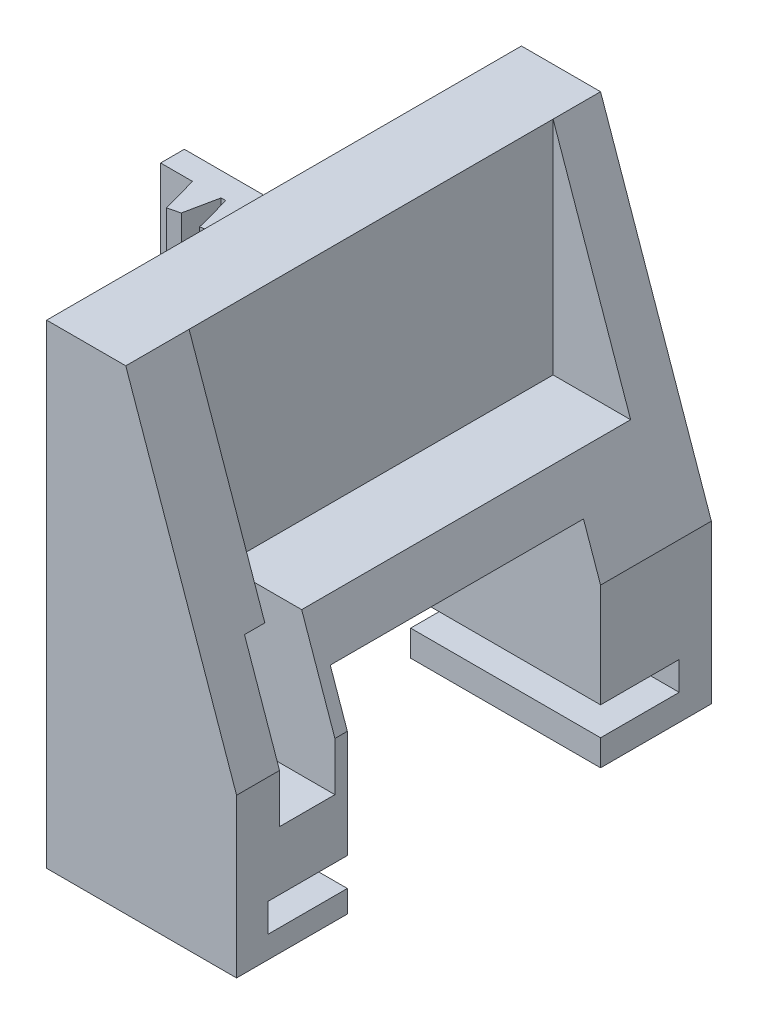
SolidWorks part; units mm, degrees
ref_plane "Front Plane" through (0, 0, 0) normal (0, 0, 1) x (1, 0, 0)
ref_plane "Top Plane" through (0, 0, 0) normal (0, 1, 0) x (1, 0, 0)
ref_plane "Right Plane" through (0, 0, 0) normal (1, 0, 0) x (0, 0, -1)
sketch "Sketch1" plane through (0, 0, 0) normal (0, 0, 1) x (1, 0, 0)
  line L0 (0, 0) -> (0, -30)
  line L1 (0, -30) -> (12, -30)
  line L2 (12, -30) -> (12, -20)
  line L3 (12, -20) -> (5, 0)
  line L4 (5, 0) -> (0, 0)
  dimension "D1" = 30
  dimension "D2" = 12
  dimension "D3" = 10
  dimension "D4" = 5
extrude "Boss-Extrude1" add sketch "Sketch1" against normal blind 30
sketch "Sketch4" plane through (0, 0, 0) normal (-1, 0, 0) x (0, 0, 1)
  line L0 (-30, 0) -> (-30, -30) construction
  line L1 (-23, -16.9179) -> (-7, -16.9179)
  line L2 (-23, -16.9179) -> (-23, -30.9179)
  line L3 (-23, -30.9179) -> (-7, -30.9179)
  line L4 (-7, -16.9179) -> (-7, -30.9179)
  point P4 (-23, -23.9179)
  dimension "D1" = 16
  dimension "D2" = 14
  dimension "D3" = 7
extrude "Cut-Extrude2" cut sketch "Sketch4" against normal blind 25 contours L2 L1 L4 L3
sketch "Sketch5" plane through (0, 0, 0) normal (-1, 0, 0) x (0, 0, 1)
  line L0 (-7, -16.9179) -> (-7, -30) construction
  line L1 (-7, -26.8) -> (-2, -26.8)
  line L2 (-7, -26.8) -> (-7, -28.6)
  line L3 (-7, -28.6) -> (-2, -28.6)
  line L4 (-2, -26.8) -> (-2, -28.6)
  line L5 (-7, -30) -> (0, -30) construction
  dimension "D1" = 1.8
  dimension "D2" = 5
  dimension "D3" = 1.4
extrude "Cut-Extrude3" cut sketch "Sketch5" against normal blind 15
ref_plane "Plane1" through (0, 0, -15.5) normal (0, 0, 1) x (1, 0, 0)
sketch "Sketch6" plane through (0, 0, -15.5) normal (0, 0, 1) x (1, 0, 0)
  line L0 (5, 0) -> (5, -14)
  line L1 (5, -14) -> (9.9, -14)
  line L2 (12, -20) -> (5, 0) construction
  line L3 (9.9, -14) -> (5, 0)
  dimension "D1" = 14
extrude "Cut-Extrude4" cut sketch "Sketch6" against normal mid plane 23
ref_plane "Plane2" through (0, -22, 0) normal (0, 1, 0) x (1, 0, 0)
sketch "Sketch7" plane through (0, -22, 0) normal (0, 1, 0) x (1, 0, 0)
  line L0 (0, 27.7) -> (-19, 27.7)
  line L1 (0, 30) -> (0, 0) construction
  line L3 (0, 27.7) -> (0, 26.2)
  line L4 (0, 26.2) -> (-0.5, 26.2)
  line L47 (-0.5, 26.2) -> (-0.9304, 24.1151)
  line L62 (-6.6, 15.5) -> (6.6, 15.5) construction
  line L108 (-19, 26.2) -> (-19, 27.7)
  line L112 (-0.9304, 24.1151) -> (-1.6865, 23.9276)
  line L113 (-2.3144, 26.2) -> (-2.597, 26.2)
  line L114 (-3.0274, 24.1151) -> (-3.7835, 23.9276)
  line L115 (-2.597, 26.2) -> (-3.0274, 24.1151)
  line L116 (-5.1244, 24.1151) -> (-5.8805, 23.9276)
  line L117 (-4.694, 26.2) -> (-5.1244, 24.1151)
  line L118 (-7.2214, 24.1151) -> (-7.9775, 23.9276)
  line L119 (-6.791, 26.2) -> (-7.2214, 24.1151)
  line L120 (-9.3184, 24.1151) -> (-10.0745, 23.9276)
  line L121 (-8.888, 26.2) -> (-9.3184, 24.1151)
  line L122 (-11.4154, 24.1151) -> (-12.1715, 23.9276)
  line L123 (-10.985, 26.2) -> (-11.4154, 24.1151)
  line L124 (-13.5124, 24.1151) -> (-14.2685, 23.9276)
  line L125 (-13.082, 26.2) -> (-13.5124, 24.1151)
  line L126 (-4.4114, 26.2) -> (-4.694, 26.2)
  line L127 (-6.5085, 26.2) -> (-6.791, 26.2)
  line L128 (-8.6055, 26.2) -> (-8.888, 26.2)
  line L129 (-10.7025, 26.2) -> (-10.985, 26.2)
  line L130 (-12.7995, 26.2) -> (-13.082, 26.2)
  line L132 (-15.6094, 24.1151) -> (-16.3655, 23.9276)
  line L133 (-15.179, 26.2) -> (-15.6094, 24.1151)
  line L134 (-14.8965, 26.2) -> (-15.179, 26.2)
  line L135 (-16.9935, 26.2) -> (-19, 26.2)
  arc A0 (-1.6865, 23.9276) -> (-2.3144, 26.2) centre (-44.8671, 13.2176) ccw
  arc A1 (-3.7835, 23.9276) -> (-4.4114, 26.2) centre (-46.9641, 13.2176) ccw
  arc A2 (-5.8805, 23.9276) -> (-6.5085, 26.2) centre (-49.0611, 13.2176) ccw
  arc A3 (-7.9775, 23.9276) -> (-8.6055, 26.2) centre (-51.1581, 13.2176) ccw
  arc A4 (-10.0745, 23.9276) -> (-10.7025, 26.2) centre (-53.2551, 13.2176) ccw
  arc A5 (-12.1715, 23.9276) -> (-12.7995, 26.2) centre (-55.3521, 13.2176) ccw
  arc A6 (-14.2685, 23.9276) -> (-14.8965, 26.2) centre (-57.4491, 13.2176) ccw
  arc A7 (-16.3655, 23.9276) -> (-16.9935, 26.2) centre (-59.5461, 13.2176) ccw
  dimension "D1" = 7
  dimension "D4" = 8
  dimension "D2" = 19
  dimension "D3" = 1.5
  dimension "D6" = 0.5
  dimension "D7" = 12.2
extrude "Boss-Extrude2" add sketch "Sketch7" along normal blind 8
sketch "Sketch8" plane through (0, 0, 0) normal (-1, 0, 0) x (0, 0, 1)
  line L0 (-6.2141, -13.6747) -> (-2.7141, -13.6747)
  line L6 (-2.7141, -13.6747) -> (-2.7141, -23.0747)
  line L7 (-2.7141, -23.0747) -> (-6.2141, -23.0747)
  line L9 (-6.2141, -23.0747) -> (-6.2141, -13.6747)
  dimension "D1" = 3.5
  dimension "D2" = 9.4
extrude "Cut-Extrude5" cut sketch "Sketch8" against normal through all
sketch "Sketch9" plane through (0, 0, 0) normal (-1, 0, 0) x (0, 0, 1)
  line L1 (-27.9704, -26.5537) -> (-22.9704, -26.5537)
  line L2 (-27.9704, -26.5537) -> (-27.9704, -28.3537)
  line L3 (-27.9704, -28.3537) -> (-22.9704, -28.3537)
  line L4 (-22.9704, -26.5537) -> (-22.9704, -28.3537)
  dimension "D1" = 1.8
  dimension "D2" = 5
extrude "Cut-Extrude6" cut sketch "Sketch9" against normal through all
